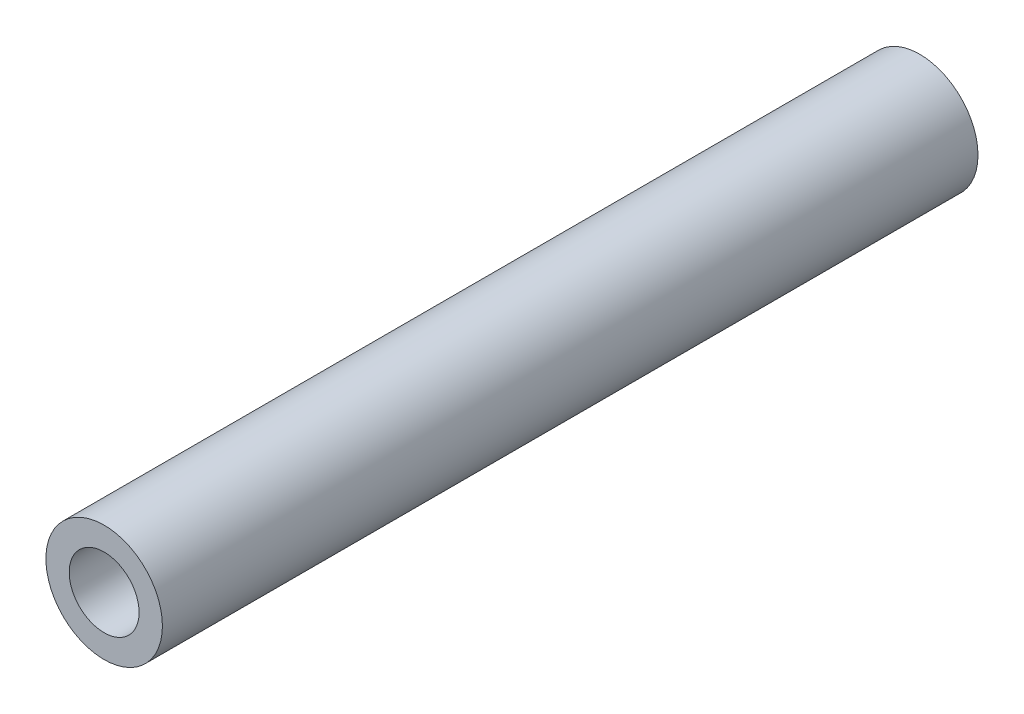
SolidWorks part; units mm, degrees
material "AISI 4340 Steel, normalized"
ref_plane "Front Plane" through (0, 0, 0) normal (0, 0, 1) x (1, 0, 0)
ref_plane "Top Plane" through (0, 0, 0) normal (0, 1, 0) x (1, 0, 0)
ref_plane "Right Plane" through (0, 0, 0) normal (1, 0, 0) x (0, 0, -1)
sketch "Sketch1" plane through (0, 0, 0) normal (0, 0, 1) x (1, 0, 0)
  circle A0 centre (0, 0) radius 1
  circle A1 centre (0, 0) radius 0.6
extrude "Installed_Spring_Pin" add sketch "Sketch1" along normal blind 14 from offset 7
